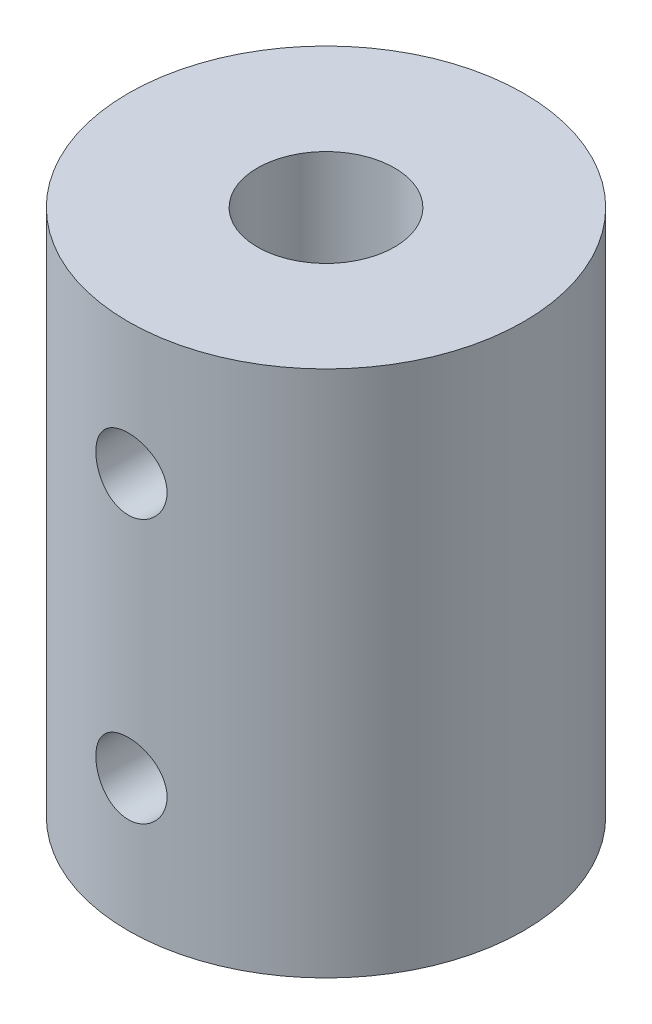
SolidWorks part; units mm, degrees
ref_plane "Front Plane" through (0, 0, 0) normal (0, 0, 1) x (1, 0, 0)
ref_plane "Top Plane" through (0, 0, 0) normal (0, 1, 0) x (1, 0, 0)
ref_plane "Right Plane" through (0, 0, 0) normal (1, 0, 0) x (0, 0, -1)
sketch "Sketch1" plane through (0, 0, 0) normal (0, 1, 0) x (1, 0, 0)
  circle A0 centre (0, 0) radius 7.5
  dimension "D1" = 15
extrude "Boss-Extrude1" add sketch "Sketch1" along normal mid plane 20
sketch "Sketch2" plane through (0, 10, 0) normal (0, 1, 0) x (1, 0, 0)
  circle A0 centre (0, 0) radius 2.6
  dimension "D1" = 5.2
extrude "Cut-Extrude1" cut sketch "Sketch2" against normal up to surface (10 mm away)
sketch "Sketch3" plane through (0, -10, 0) normal (0, -1, 0) x (1, 0, 0)
  circle A0 centre (0, 0) radius 4.1
  dimension "D1" = 8.2
extrude "Cut-Extrude2" cut sketch "Sketch3" against normal up to surface (10 mm away)
ref_plane "Plane1" through (0, 0, 10) normal (0, 0, 1) x (1, 0, 0)
sketch "Sketch4" plane through (0, 0, 10) normal (0, 0, 1) x (1, 0, 0)
  line L0 (0, 10) -> (0, 0) construction
  line L1 (2.6, 10) -> (-2.6, 10) construction
  line L2 (0, 0) -> (0, -10) construction
  line L3 (-7.5, -10) -> (7.5, -10) construction
  point P8 (0, -5)
  point P9 (0, 5)
hole_wizard "Ø2.7 (2.7) Diameter Hole1" positions "Sketch4" profile "Sketch5" hole size "Ø2.7" standard "ANSI Metric" end condition through all
sketch "Sketch5" plane through (0, 5, 10) normal (1, 0, 0) x (0, -1, 0)
  line L0 (0, 0) -> (0, 17.5)
  line L1 (0, 17.5) -> (1.35, 17.5)
  line L2 (1.35, 17.5) -> (1.35, 0)
  line L5 (1.35, 0) -> (0, 0)
  line L11 (0, -6.35) -> (0, 107.95) construction
  dimension "Thru Hole Dia." = 2.7
  dimension "Thru Hole Depth" = 17.5
